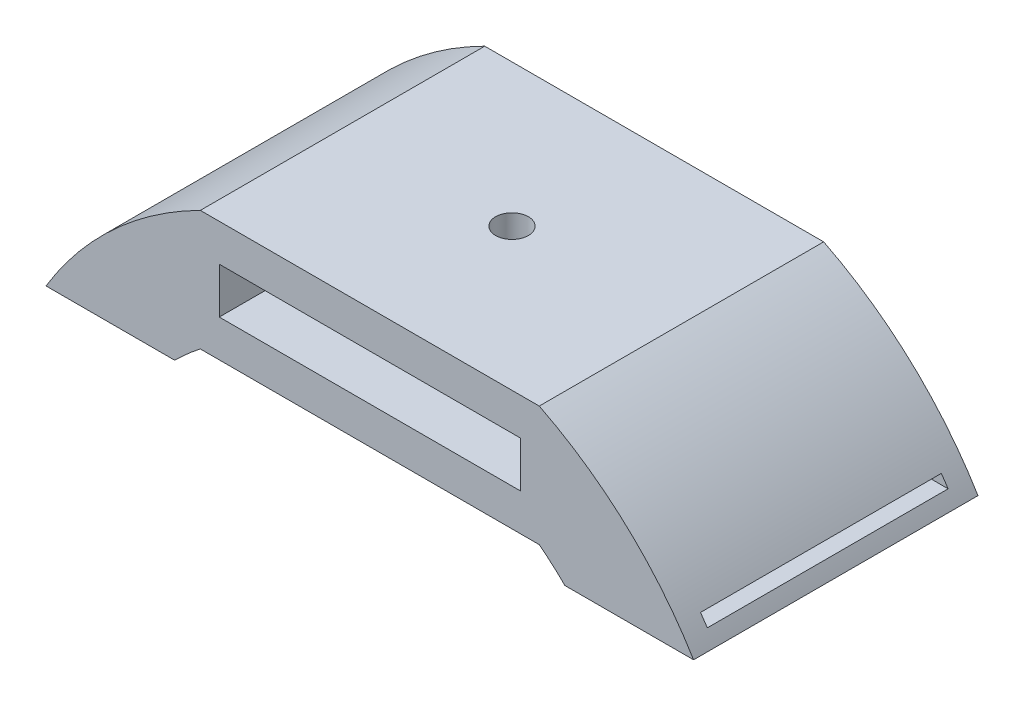
SolidWorks part; units mm, degrees
ref_plane "Front Plane" through (0, 0, 0) normal (0, 0, 1) x (1, 0, 0)
ref_plane "Top Plane" through (0, 0, 0) normal (0, 1, 0) x (1, 0, 0)
ref_plane "Right Plane" through (0, 0, 0) normal (1, 0, 0) x (0, 0, -1)
sketch "Sketch1" plane through (0, 0, 0) normal (0, 1, 0) x (1, 0, 0)
  line L0 (-18.4663, 7.6314) -> (17.2837, 7.6314) construction
  line L1 (-18.4663, 22.6314) -> (17.2837, 22.6314)
  line L2 (-18.4663, 22.6314) -> (-18.4663, -7.3686)
  line L3 (-18.4663, -7.3686) -> (17.2837, -7.3686)
  line L4 (17.2837, 22.6314) -> (17.2837, -7.3686)
  line L5 (-0.5913, 22.6314) -> (-0.5913, -7.3686) construction
  circle A0 centre (-0.5913, 7.6314) radius 1.725
  point P4 (-18.4663, 7.6314)
  point P5 (-0.5913, 22.6314)
  dimension "D3" = 3.45
  dimension "D1" = 35.75
  dimension "D2" = 30
extrude "Boss-Extrude1" add sketch "Sketch1" along normal blind 8.83 and the other way blind 3.83
sketch "Sketch2" plane through (0, 0, -22.6314) normal (0, 0, -1) x (-1, 0, 0)
  line L0 (0.5913, 8.83) -> (0.5913, -3.83) construction
  line L1 (16.4663, 4.915) -> (-15.2837, 4.915)
  line L2 (16.4663, 4.915) -> (16.4663, 0.085)
  line L3 (16.4663, 0.085) -> (-15.2837, 0.085)
  line L4 (-15.2837, 4.915) -> (-15.2837, 0.085)
  line L5 (-17.2837, 8.83) -> (18.4663, 8.83) construction
  line L6 (-17.2837, -3.83) -> (18.4663, -3.83) construction
  line L7 (18.4663, 2.5) -> (-17.2837, 2.5) construction
  line L8 (18.4663, 8.83) -> (18.4663, -3.83) construction
  line L9 (-17.2837, 8.83) -> (-17.2837, -3.83) construction
  point P16 (-15.2837, 2.5)
  point P17 (0.5913, 4.915)
  dimension "D1" = 4.83
  dimension "D3" = 31.75
extrude "Cut-Extrude1" cut sketch "Sketch2" against normal through all
sketch "Sketch4" plane through (0, 0, 0) normal (0, 0, 1) x (1, 0, 0)
  line L0 (33.5623, -6.2124) -> (19.9877, -6.2124)
  line L1 (-18.4663, -3.83) -> (17.2837, -3.83) construction
  line L3 (-21.1703, -6.2124) -> (-34.7449, -6.2124)
  line L5 (-18.4663, -3.83) -> (-18.4663, 8.83)
  line L6 (17.2837, 8.83) -> (17.2837, -3.83)
  arc A1 (19.9877, -6.2124) -> (17.2837, -3.83) centre (-0.5913, -26.8433) ccw
  arc A2 (33.5623, -6.2124) -> (17.2837, 8.83) centre (-0.5913, -26.8433) ccw
  arc A3 (-18.4663, 8.83) -> (-34.7449, -6.2124) centre (-0.5913, -26.8433) ccw
  arc A4 (-18.4663, -3.83) -> (-21.1703, -6.2124) centre (-0.5913, -26.8433) ccw
  point P0 (-0.5913, -3.83)
  point P11 (0, 0)
  point P13 (0, 0)
extrude "Boss-Extrude4" add sketch "Sketch4" along normal through all and the other way through all contours A1 L6 A2 L0 | A4 L3 A3 L5
ref_plane "Plane3" through (-34.7449, 0, 0) normal (-1, 0, 0) x (0, 0, 1)
sketch "Sketch7" plane through (-34.7449, 0, 0) normal (-1, 0, 0) x (0, 0, 1)
  line L0 (7.3686, -6.2124) -> (-22.6314, -6.2124) construction
  line L1 (-20.3314, -3.8156) -> (5.0686, -3.8156)
  line L2 (-20.3314, -3.8156) -> (-20.3314, -4.8656)
  line L3 (-20.3314, -4.8656) -> (5.0686, -4.8656)
  line L4 (5.0686, -3.8156) -> (5.0686, -4.8656)
  point P4 (-7.6314, -4.8656)
  point P5 (-7.6314, -6.2124)
  dimension "D1" = 25.4
  dimension "D2" = 1.05
extrude "Cut-Extrude2" cut sketch "Sketch7" against normal through all
sketch "Sketch8" plane through (0, -3.83, 0) normal (0, -1, 0) x (1, 0, 0)
  circle A0 centre (-0.5913, -7.6314) radius 2.85
  dimension "D1" = 5.7
extrude "Cut-Extrude3" cut sketch "Sketch8" against normal blind 3
